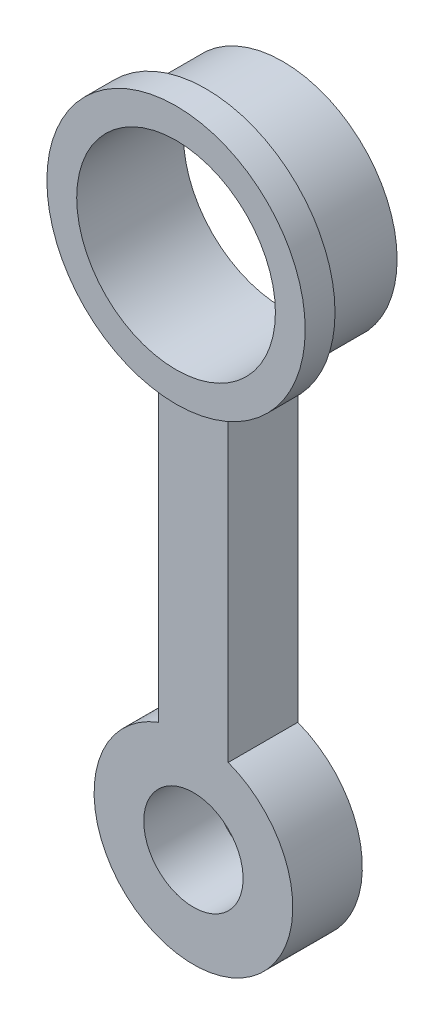
SolidWorks part; units mm, degrees
ref_plane "Alzado" through (0, 0, 0) normal (0, 0, 1) x (1, 0, 0)
ref_plane "Planta" through (0, 0, 0) normal (0, 1, 0) x (1, 0, 0)
ref_plane "Vista lateral" through (0, 0, 0) normal (1, 0, 0) x (0, 0, -1)
sketch "Croquis1" plane through (0, 0, 0) normal (0, 0, 1) x (1, 0, 0)
  circle A0 centre (0, 0) radius 10
  dimension "D1" = 20
extrude "Saliente-Extruir1" add sketch "Croquis1" along normal blind 3
sketch "Croquis2" plane through (0, 0, 3) normal (0, 0, 1) x (1, 0, 0)
  circle A0 centre (0, 0) radius 2.5
  circle A1 centre (0, 0) radius 4
  circle A2 centre (0, 0) radius 11.5
  circle A3 centre (0, 0) radius 10
  circle M1 centre (0, 0) radius 10
  dimension "D1" = 5
  dimension "D2" = 8
  dimension "D3" = 23
extrude "Saliente-Extruir3" add sketch "Croquis2" along normal blind 8 separate body contours A2 M1
sketch "Croquis3" plane through (0, 0, 3) normal (0, 0, -1) x (-1, 0, 0)
  circle A0 centre (0, 0) radius 11.5
  circle A1 centre (0, 0) radius 10
extrude "Saliente-Extruir4" add sketch "Croquis3" along normal up to surface (3 mm away) up to face at (10, 0, 0)
ref_plane "Plano1" through (0, 11.5, 0) normal (0, 1, 0) x (1, 0, 0)
sketch "Croquis7" plane through (0, 0, 11) normal (0, 0, 1) x (1, 0, 0)
  line L0 (0, 11.5) -> (0, 0) construction
  line L1 (6.05, 11.5) -> (-6.05, 11.5) construction
  line L2 (0, 0) -> (11.5, 0) construction
  circle A0 centre (0, 0) radius 11.5 construction
ref_plane "Plano2" through (0, 11.5, 0) normal (0, 1, 0) x (1, 0, 0)
ref_plane "Plano3" through (0, 11.5, 0) normal (0, 1, 0) x (1, 0, 0)
sketch "Croquis9" plane through (0, 0, 11) normal (0, 0, 1) x (1, 0, 0)
  line L0 (11.5, 0) -> (11.5, 3)
  line L1 (11.5, 3) -> (12.0602, 3)
  line L2 (12.0602, 3) -> (12.0602, -3)
  line L3 (11.5, 0) -> (11.5, -3)
  line L4 (12.0602, -3) -> (11.5, -3)
  dimension "D1" = 3
  dimension "D2" = 3
extrude "Saliente-Extruir5" add sketch "Croquis9" against normal blind 8 separate body
sketch "Croquis11" plane through (0, 0, 11) normal (0, 0, 1) x (1, 0, 0)
  line L1 (11.5, 3) -> (12.0602, 3)
  line L2 (11.5, 3) -> (11.5, -3)
  line L3 (11.5, -3) -> (12.0602, -3)
  line L4 (12.0602, 3) -> (12.0602, -3)
extrude "Cortar-Extruir3" cut sketch "Croquis11" against normal blind 8
ref_plane "Plano4" through (-11.5, 0, 0) normal (-1, 0, 0) x (0, 0, 1)
sketch "Croquis12" plane through (0, 0, 3) normal (0, 0, 1) x (1, 0, 0)
  line L0 (0, 0) -> (0, -11.5) construction
  line L1 (0, -11.5) -> (-2.5, -11.5)
  line L2 (0, -11.5) -> (2.5, -11.5)
  line L3 (-2.5, -11.5) -> (-2.5, -10.878)
  line L4 (-2.5, -11.5) -> (2.5, -11.5)
  line L5 (-2.5, -11.5) -> (-2.5, -61.5)
  line L6 (-2.5, -61.5) -> (2.5, -61.5)
  line L7 (2.5, -11.5) -> (2.5, -61.5)
  line L8 (-2.5, -10.878) -> (0, -10.878)
  line L9 (0, -10.878) -> (0, -11.5)
  line L10 (0, -10.878) -> (2.5, -10.878)
  line L11 (2.5, -10.878) -> (2.5, -11.5)
  circle A0 centre (0, 0) radius 11.5 construction
  dimension "D1" = 2.5
  dimension "D2" = 2.5
  dimension "D3" = 50
extrude "Saliente-Extruir6" add sketch "Croquis12" against normal up to surface (3 mm away) contours L9 L8 L3 L1 | L11 L10 L9 L2 | L7 L2 L1 L5 L6 up to face at (11.5, 0, 0)
sketch "Croquis13" plane through (0, 0, 3) normal (0, 0, 1) x (1, 0, 0)
  line L1 (-2.5, -11.225) -> (2.5, -11.225)
  line L2 (-2.5, -11.225) -> (-2.5, -61.5)
  line L3 (-2.5, -61.5) -> (2.5, -61.5)
  line L4 (2.5, -11.225) -> (2.5, -61.5)
extrude "Saliente-Extruir7" add sketch "Croquis13" along normal up to surface (8 mm away) up to face at (10, 0, 11)
sketch "Croquis15" plane through (2.5, 0, 0) normal (1, 0, 0) x (0, 0, -1)
  line L0 (0, -11.225) -> (-11, -11.225) construction
  line L1 (-11, -61.5) -> (-9, -61.5)
  line L2 (-11, -61.5) -> (-11, -11.225)
  line L3 (-11, -11.225) -> (-9, -11.225)
  line L4 (-9, -61.5) -> (-9, -11.225)
  line L6 (0, -61.5) -> (-2, -61.5)
  line L7 (0, -61.5) -> (0, -11.225)
  line L8 (0, -11.225) -> (-2, -11.225)
  line L9 (-2, -61.5) -> (-2, -11.225)
  dimension "D1" = 2
  dimension "D2" = 2
extrude "Cortar-Extruir4" cut sketch "Croquis15" against normal blind 8
sketch "Croquis16" plane through (0, 0, 9) normal (0, 0, 1) x (1, 0, 0)
  line L0 (-2.5, -61.5) -> (-3.5, -61.5)
  line L1 (2.5, -61.5) -> (3.5, -61.5)
  line L2 (-3.5, -61.5) -> (-3.5, -10.233)
  line L3 (-3.5, -10.233) -> (3.5, -10.233)
  line L4 (3.5, -10.233) -> (3.5, -61.5)
  line L9 (-2.5, -61.5) -> (2.5, -61.5)
  line L10 (2.5, -61.5) -> (2.5, -11.225)
  line L11 (2.5, -11.225) -> (-2.5, -11.225)
  line L12 (-2.5, -11.225) -> (-2.5, -61.5)
  line L13 (-2.5, -61.5) -> (2.5, -61.5)
  dimension "D1" = 1
  dimension "D2" = 1
  dimension "D3" = 0
extrude "Saliente-Extruir8" add sketch "Croquis16" against normal up to surface (7 mm away) up to face at (0, -36.3625, 2)
sketch "Croquis21" plane through (0, 0, 2) normal (0, 0, -1) x (-1, 0, 0)
  line L0 (0, -11.225) -> (0, -52.725) construction
  line L1 (2.5, -11.225) -> (-2.5, -11.225) construction
  circle A0 centre (0, -52.725) radius 10
  dimension "D2" = 20
  dimension "D1" = 41.5
extrude "Saliente-Extruir9" add sketch "Croquis21" against normal up to surface (7 mm away) up to face at (0, -27.8969, 9)
sketch "Croquis22" plane through (0, 0, 2) normal (0, 0, -1) x (-1, 0, 0)
  circle A0 centre (0, -52.725) radius 5
  dimension "D1" = 10
extrude "Cortar-Extruir5" cut sketch "Croquis22" against normal blind 30
sketch "Croquis23" plane through (0, 0, 11) normal (0, 0, 1) x (1, 0, 0)
  line L0 (-2.5, -11.225) -> (2.5, -11.225) construction
  line L1 (-2.5, -11.225) -> (2.5, -11.225)
  arc A0 (2.5, -11.225) -> (-2.5, -11.225) centre (0, 0) ccw construction
  arc A1 (2.5, -11.225) -> (-2.5, -11.225) centre (0, 0) ccw
  circle A2 centre (0, 0) radius 10 construction
  circle A3 centre (0, 0) radius 10
extrude "Saliente-Extruir10" add sketch "Croquis23" along normal blind 1.25
sketch "Croquis24" plane through (0, 0, 12.25) normal (0, 0, 1) x (1, 0, 0)
  line L0 (-2.5, -11.225) -> (2.5, -11.225) construction
  line L1 (-2.5, -11.225) -> (2.5, -11.225)
  circle A0 centre (0, 0) radius 10 construction
  arc A1 (2.5, -11.225) -> (-2.5, -11.225) centre (0, 0) ccw construction
  circle A2 centre (0, 0) radius 10
  arc A3 (2.5, -11.225) -> (-2.5, -11.225) centre (0, 0) ccw
extrude "Cortar-Extruir6" cut sketch "Croquis24" against normal blind 1.5
sketch "Croquis25" plane through (0, 0, 10.75) normal (0, 0, 1) x (1, 0, 0)
  circle A0 centre (0, 0) radius 13
  arc A1 (2.5, -11.225) -> (-2.5, -11.225) centre (0, 0) ccw construction
  arc A2 (2.5, -11.225) -> (-2.5, -11.225) centre (0, 0) ccw
  arc M2 (2.5, -11.225) -> (-2.5, -11.225) centre (0, 0) ccw
  line M3 (-2.5, -11.225) -> (2.5, -11.225)
  dimension "D1" = 26
  dimension "D2" = 23
extrude "Saliente-Extruir11" add sketch "Croquis25" against normal blind 3 contours A0 M2 M3
sketch "Croquis30" plane through (0, 0, 3) normal (0, 0, 1) x (1, 0, 0)
  circle A0 centre (0, 0) radius 10
extrude "Cortar-Extruir14" cut sketch "Croquis30" against normal blind 10
sketch "Croquis31" plane through (0, 0, 0) normal (0, 0, -1) x (-1, 0, 0)
  circle A0 centre (0, 0) radius 11.5
  circle A1 centre (0, 0) radius 10 construction
  circle A2 centre (0, 0) radius 10
extrude "Saliente-Extruir12" add sketch "Croquis31" against normal up to surface (7.75 mm away) up to face at (0, 0.2564, 7.75)
